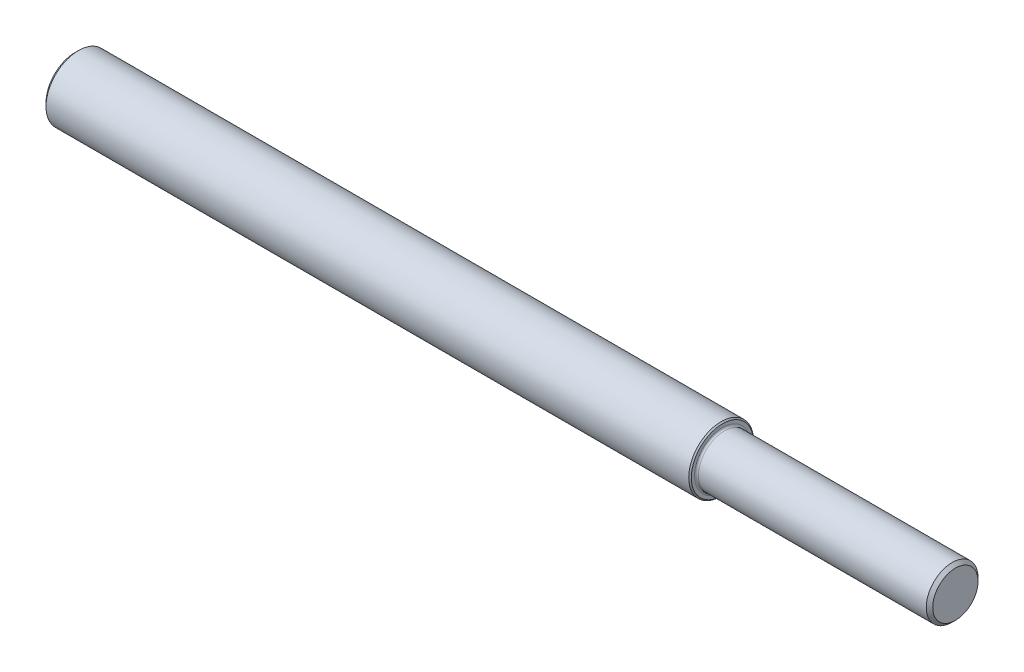
SolidWorks part; units mm, degrees
ref_plane "Front Plane" through (0, 0, 0) normal (0, 0, 1) x (1, 0, 0)
ref_plane "Top Plane" through (0, 0, 0) normal (0, 1, 0) x (1, 0, 0)
ref_plane "Right Plane" through (0, 0, 0) normal (1, 0, 0) x (0, 0, -1)
ref_plane "Plane1" through (0, 0, 0) normal (0, 0, 1) x (1, 0, 0)
sketch "Sketch1" plane through (0, 0, 0) normal (0, 0, 1) x (1, 0, 0)
  line L0 (0, 0) -> (0, 4.5)
  line L1 (0, 4.5) -> (0.5, 5)
  line L2 (0.5, 5) -> (99.8, 5)
  line L3 (99.8, 5) -> (100, 4.8)
  line L4 (100, 4.8) -> (100, 4.3)
  line L5 (100.3, 4) -> (135.5, 4)
  line L6 (135.5, 4) -> (136, 3.5)
  line L7 (136, 3.5) -> (136, 0)
  line L8 (136, 0) -> (0, 0)
  line L9 (136, 0) -> (0, 0) construction
  arc A0 (100, 4.3) -> (100.3, 4) centre (100.3, 4.3) ccw
revolve "Revolve1" add sketch "Sketch1" angle 360 about L9
